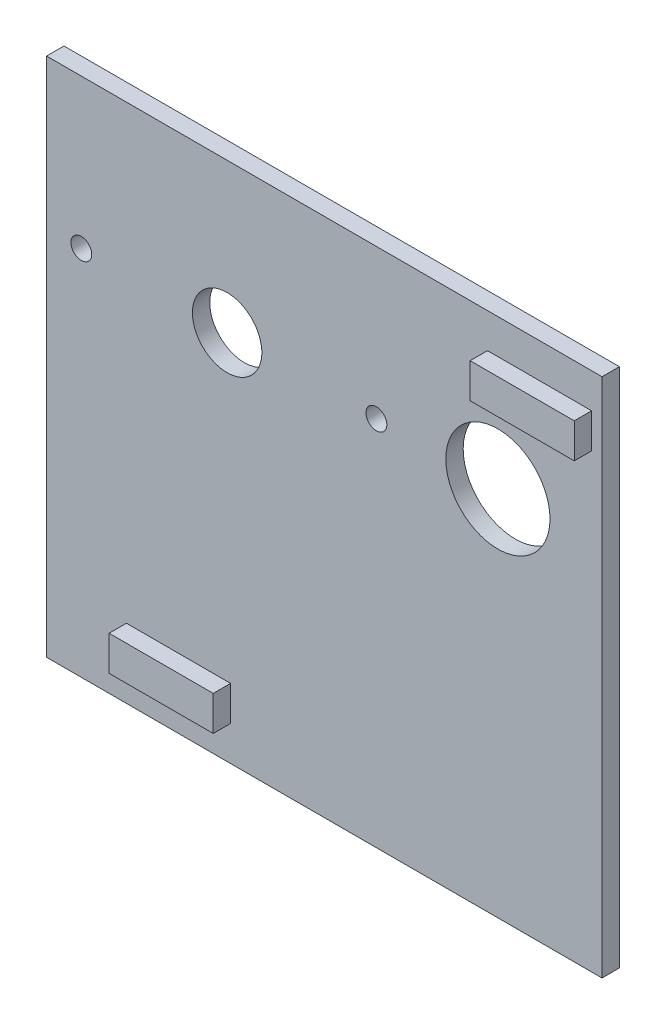
SolidWorks part; units mm, degrees
ref_plane "Front Plane" through (0, 0, 0) normal (0, 0, 1) x (1, 0, 0)
ref_plane "Top Plane" through (0, 0, 0) normal (0, 1, 0) x (1, 0, 0)
ref_plane "Right Plane" through (0, 0, 0) normal (1, 0, 0) x (0, 0, -1)
sketch "Sketch1" plane through (0, 0, 0) normal (0, 0, 1) x (1, 0, 0)
  line L1 (0, 0) -> (-160, 0)
  line L2 (0, 0) -> (0, -150)
  line L3 (0, -150) -> (-160, -150)
  line L4 (-160, 0) -> (-160, -150)
  dimension "D1" = 160
  dimension "D2" = 150
extrude "Boss-Extrude1" add sketch "Sketch1" along normal blind 5
sketch "Sketch2" plane through (0, 0, 5) normal (0, 0, 1) x (1, 0, 0)
  line L0 (-160, -150) -> (0, -150) construction
  line L1 (-33, -10) -> (-3, -10)
  line L2 (-33, -10) -> (-33, -20)
  line L3 (-33, -20) -> (-3, -20)
  line L4 (-3, -10) -> (-3, -20)
  line L7 (0, 0) -> (-160, 0) construction
  line L8 (-160, 0) -> (-160, -150) construction
  line L9 (0, -150) -> (0, 0) construction
  line L12 (-137, -130) -> (-107, -130)
  line L13 (-137, -130) -> (-137, -140)
  line L14 (-137, -140) -> (-107, -140)
  line L15 (-107, -130) -> (-107, -140)
  dimension "D1" = 30
  dimension "D2" = 3
  dimension "D3" = 10
  dimension "D4" = 10
  dimension "D5" = 23
  dimension "D6" = 30
  dimension "D7" = 10
  dimension "D8" = 10
extrude "Boss-Extrude2" add sketch "Sketch2" along normal blind 5
sketch "Sketch4" plane through (0, 0, 10) normal (0, 0, 1) x (1, 0, 0)
  line L0 (0, 0) -> (-160, 0) construction
  line L1 (0, 0) -> (-160, 0) construction
  line L2 (-160, 0) -> (-160, -150) construction
  line L3 (0, -150) -> (0, 0) construction
  circle A0 centre (-150, -43) radius 3
  circle A1 centre (-108, -43) radius 10
  circle A2 centre (-65, -43) radius 3
  circle A3 centre (-30, -43) radius 15
  dimension "D1" = 6
  dimension "D2" = 20
  dimension "D3" = 6
  dimension "D4" = 43
  dimension "D5" = 43
  dimension "D6" = 43
  dimension "D7" = 10
  dimension "D8" = 52
  dimension "D9" = 95
  dimension "D10" = 30
  dimension "D11" = 30
  dimension "D12" = 43
extrude "Cut-Extrude1" cut sketch "Sketch4" against normal blind 15
